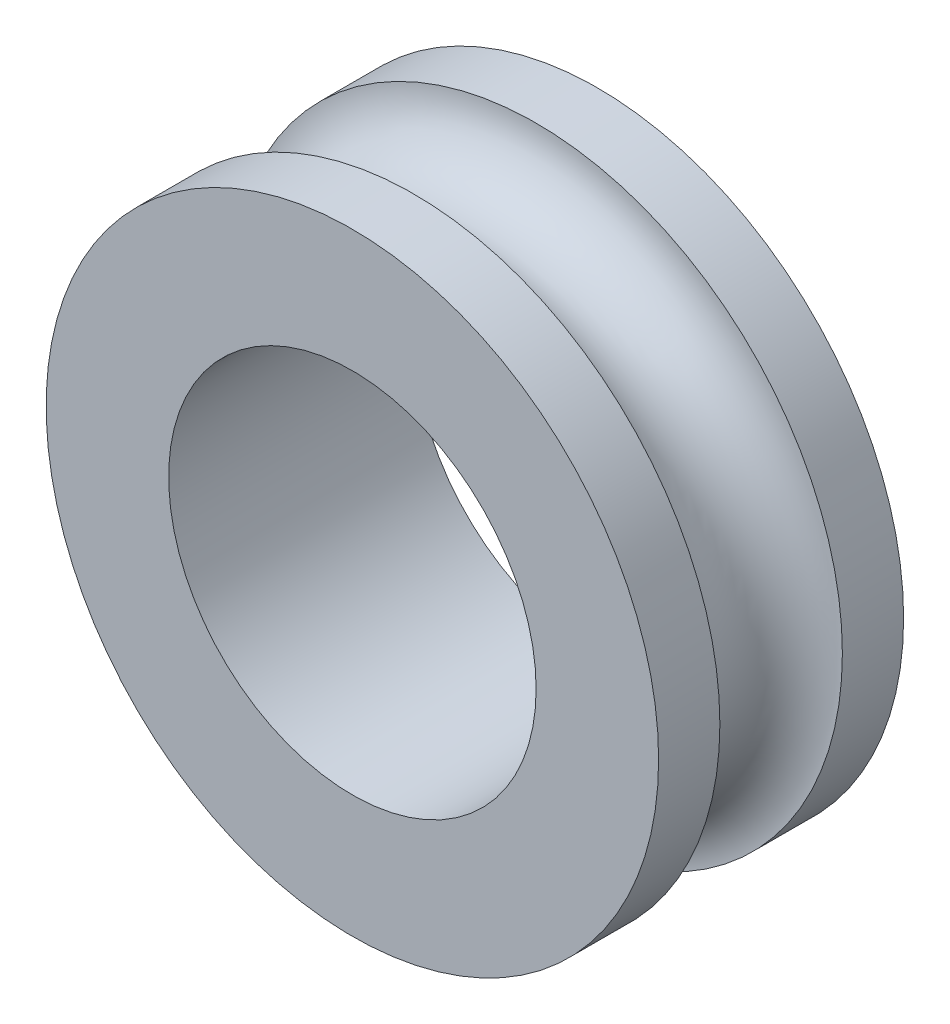
SolidWorks part; units mm, degrees
ref_plane "Front Plane" through (0, 0, 0) normal (0, 0, 1) x (1, 0, 0)
ref_plane "Top Plane" through (0, 0, 0) normal (0, 1, 0) x (1, 0, 0)
ref_plane "Right Plane" through (0, 0, 0) normal (1, 0, 0) x (0, 0, -1)
sketch "Sketch1" plane through (0, 0, 0) normal (0, 0, 1) x (1, 0, 0)
  circle A0 centre (0, 0) radius 5
  circle A1 centre (0, 0) radius 3
  dimension "D1" = 10
  dimension "D2" = 6
extrude "Boss-Extrude1" add sketch "Sketch1" along normal blind 4
sketch "Sketch2" plane through (0, 0, 0) normal (1, 0, 0) x (0, 0, -1)
  line L0 (0, 5) -> (-4, 5) construction
  line L1 (-3, 5) -> (-1, 5)
  arc A0 (-3, 5) -> (-1, 5) centre (-2, 5) ccw
  dimension "D1" = 2
revolve "Cut-Revolve1" cut sketch "Sketch2" angle 360 about axis through (0, 0, 4) along (0, 0, -1)
